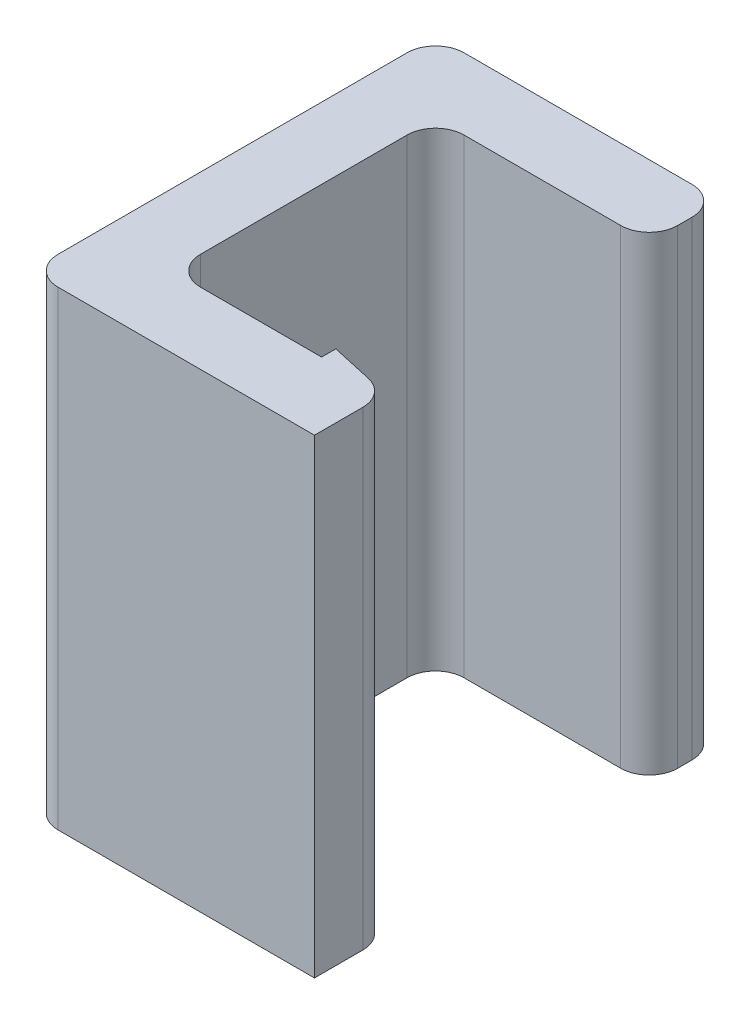
SolidWorks part; units mm, degrees
ref_plane "Front Plane" through (0, 0, 0) normal (0, 0, 1) x (1, 0, 0)
ref_plane "Top Plane" through (0, 0, 0) normal (0, 1, 0) x (1, 0, 0)
ref_plane "Right Plane" through (0, 0, 0) normal (1, 0, 0) x (0, 0, -1)
sketch "Sketch1" plane through (0, 0, 0) normal (0, 1, 0) x (1, 0, 0)
  line L0 (0, 0) -> (0, 18.5)
  line L1 (0, 18.5) -> (15, 18.5)
  line L2 (15, 18.5) -> (15, 23.5)
  line L3 (15, 23.5) -> (-5, 23.5)
  line L4 (-5, 23.5) -> (-5, -5)
  line L5 (-5, -5) -> (15, -5)
  line L6 (15, -5) -> (15, 0)
  line L7 (15, 0) -> (0, 0)
  line L8 (15, 0) -> (10.5, 1)
  line L9 (10.5, 1) -> (10.5, 0)
  line L10 (10.5, 0) -> (15, 0)
  dimension "D1" = 18.5
  dimension "D2" = 5
  dimension "D3" = 5
  dimension "D4" = 5
  dimension "D5" = 15
  dimension "D6" = 15
  dimension "D7" = 1
  dimension "D8" = 10.5
extrude "Boss-Extrude1" add sketch "Sketch1" along normal blind 33 contours L8 L9 L7 | L6 L7 L0 L1 L2 L3 L4 L5
fillet "Fillet1" radius 2 7 edges at (15, 16.5, -23.5) (-5, 16.5, 5) (-5, 16.5, -23.5) (15, 16.5, 0) (15, 16.5, -18.5) (0, 16.5, 0) (0, 16.5, -18.5)
